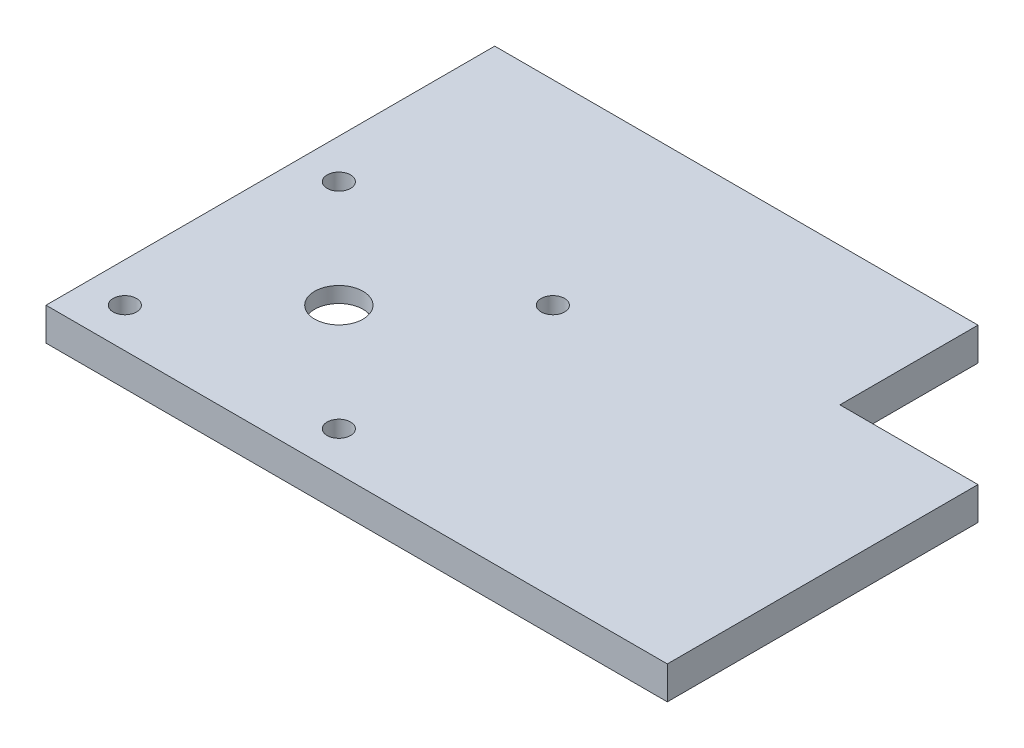
SolidWorks part; units mm, degrees
material "6061 Alloy"
ref_plane "Front Plane" through (0, 0, 0) normal (0, 0, 1) x (1, 0, 0)
ref_plane "Top Plane" through (0, 0, 0) normal (0, 1, 0) x (1, 0, 0)
ref_plane "Right Plane" through (0, 0, 0) normal (1, 0, 0) x (0, 0, -1)
sketch "Sketch1" plane through (0, 0, 0) normal (0, 1, 0) x (1, 0, 0)
  line L1 (70, 65) -> (70, 45)
  line L2 (70, 45) -> (90, 45)
  line L3 (0, 0) -> (90, 0)
  line L4 (0, 0) -> (0, 65)
  line L5 (0, 65) -> (70, 65)
  line L6 (90, 0) -> (90, 45)
  line L7 (0, 0) -> (70, 45) construction
  line L8 (0, 65) -> (90, 0) construction
  dimension "D1" = 65
  dimension "D2" = 90
  dimension "D11" = 20
  dimension "D12" = 20
extrude "Boss-Extrude1" add sketch "Sketch1" along normal blind 4.7625
sketch "Sketch3" plane through (0, 0, 0) normal (0, -1, 0) x (1, 0, 0)
  circle A0 centre (5.709, -36.709) radius 1.5 construction
  circle A1 centre (36.709, -36.709) radius 1.5 construction
  circle A2 centre (5.709, -5.709) radius 1.5 construction
  circle A3 centre (36.709, -5.709) radius 1.5 construction
  circle A4 centre (21.209, -21.209) radius 2.5 construction
  point P16 (36.709, -36.709)
  point P17 (5.709, -36.709)
  point P18 (21.209, -21.209)
  point P19 (5.709, -5.709)
  point P20 (36.709, -5.709)
hole_wizard "M3 Clearance Hole1" positions "Sketch4" profile "Sketch5" hole size "M3" standard "ANSI Metric" end condition through all
sketch "Sketch4" plane through (0, 4.7625, 0) normal (0, 1, 0) x (1, 0, 0)
  point P0 (36.709, 5.709)
  point P3 (36.709, 36.709)
  point P6 (5.709, 36.709)
  point P9 (5.709, 5.709)
sketch "Sketch5" plane through (36.709, 4.7625, -5.709) normal (1, 0, 0) x (0, 0, 1)
  line L0 (0, 0) -> (0, 4.7625)
  line L1 (0, 4.7625) -> (1.7, 4.7625)
  line L2 (1.7, 4.7625) -> (1.7, 0)
  line L5 (1.7, 0) -> (0, 0)
  line L11 (0, -6.35) -> (0, 107.95) construction
  dimension "Thru Hole Dia." = 3.4
  dimension "Thru Hole Depth" = 4.7625
hole_wizard "Ø7.0 (7) Diameter Hole1" positions "Sketch8" profile "Sketch9" hole size "Ø7.0" standard "ANSI Metric" end condition through all
sketch "Sketch8" plane through (0, 0, 0) normal (0, -1, 0) x (-1, 0, 0)
  point P0 (-21.209, 21.209)
sketch "Sketch9" plane through (21.209, 0, -21.209) normal (1, 0, 0) x (0, 0, -1)
  line L0 (0, 0) -> (0, 4.7625)
  line L1 (0, 4.7625) -> (3.5, 4.7625)
  line L2 (3.5, 4.7625) -> (3.5, 0)
  line L5 (3.5, 0) -> (0, 0)
  line L11 (0, -6.35) -> (0, 107.95) construction
  dimension "Thru Hole Dia." = 7
  dimension "Thru Hole Depth" = 4.7625
sketch "Sketch12" plane through (0, 0, 0) normal (0, -1, 0) x (1, 0, 0)
  circle A0 centre (21.209, -21.209) radius 11.5
extrude "Cut-Extrude1" cut sketch "Sketch12" against normal blind 2.5
sketch "Sketch14" plane through (0, 4.7625, 0) normal (0, 1, 0) x (1, 0, 0)
  line L0 (70, 45) -> (70, 0) construction
  line L1 (0, 0) -> (90, 0) construction
  line L2 (42.418, 21.209) -> (70, 21.209) construction
  line L4 (37.097, 42.418) -> (5.321, 42.418)
  line L5 (42.418, 5.321) -> (42.418, 37.097)
  line L6 (5.321, 0) -> (37.097, 0)
  line L7 (0, 37.097) -> (0, 5.321)
  line L8 (37.097, 42.418) -> (5.321, 42.418)
  line L9 (42.418, 5.321) -> (42.418, 37.097)
  line L10 (5.321, 0) -> (37.097, 0)
  line L11 (0, 37.097) -> (0, 5.321)
  line L12 (52.709, 31.209) -> (59.709, 31.209)
  line L13 (52.709, 31.209) -> (52.709, 11.209)
  line L14 (52.709, 11.209) -> (59.709, 11.209)
  line L15 (59.709, 31.209) -> (59.709, 11.209)
  line L16 (52.709, 31.209) -> (59.709, 11.209) construction
  line L17 (52.709, 11.209) -> (59.709, 31.209) construction
  circle A0 centre (21.209, 21.209) radius 6.1 construction
  circle A1 centre (21.209, 21.209) radius 6.1 construction
  circle A2 centre (21.209, 21.209) radius 7.5 construction
  circle A3 centre (21.209, 21.209) radius 7.5
  arc A4 (5.321, 42.418) -> (0, 37.097) centre (21.209, 21.209) ccw
  arc A5 (42.418, 37.097) -> (37.097, 42.418) centre (21.209, 21.209) ccw
  arc A6 (37.097, 0) -> (42.418, 5.321) centre (21.209, 21.209) ccw
  arc A7 (0, 5.321) -> (5.321, 0) centre (21.209, 21.209) ccw
  arc A8 (5.321, 42.418) -> (0, 37.097) centre (21.209, 21.209) ccw
  arc A9 (42.418, 37.097) -> (37.097, 42.418) centre (21.209, 21.209) ccw
  arc A10 (37.097, 0) -> (42.418, 5.321) centre (21.209, 21.209) ccw
  arc A11 (0, 5.321) -> (5.321, 0) centre (21.209, 21.209) ccw
  circle A12 centre (59.709, 31.209) radius 6.1 construction
  circle A13 centre (59.709, 31.209) radius 7.5
  circle A14 centre (52.709, 11.209) radius 6.1 construction
  circle A15 centre (52.709, 11.209) radius 7.5
  point P25 (56.209, 21.209)
  point P26 (67.209, 31.209)
  dimension "D2" = 7
  dimension "D3" = 20
  dimension "D1" = 0
